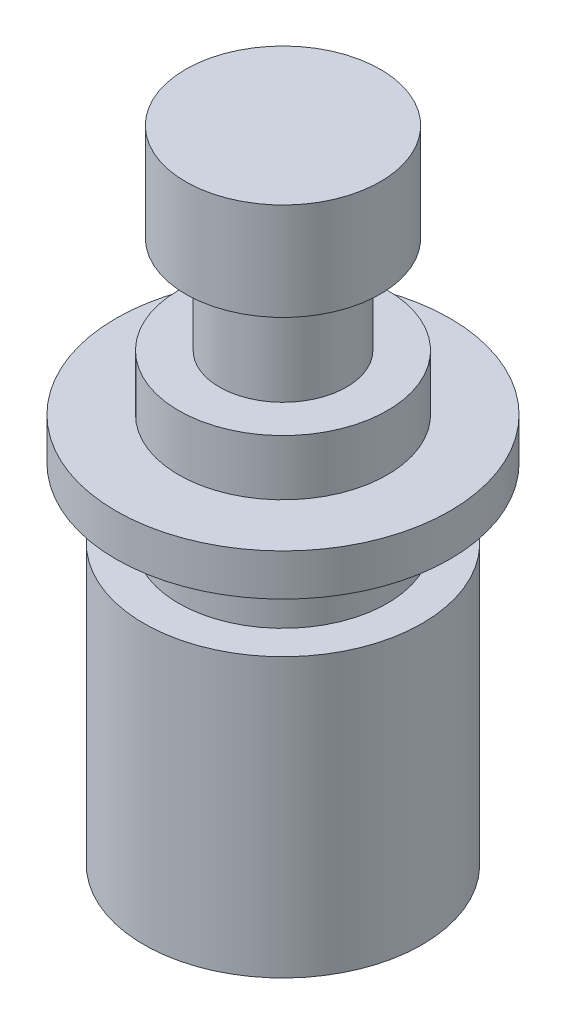
SolidWorks part; units mm, degrees
ref_plane "Plan de face" through (0, 0, 0) normal (0, 0, 1) x (1, 0, 0)
ref_plane "Plan de dessus" through (0, 0, 0) normal (0, 1, 0) x (1, 0, 0)
ref_plane "Plan de droite" through (0, 0, 0) normal (1, 0, 0) x (0, 0, -1)
sketch "Esquisse1" plane through (0, 0, 0) normal (0, 0, 1) x (1, 0, 0)
  line L0 (0, -72.5172) -> (0, -95.5172) construction
  line L1 (0, -72.5172) -> (3.5, -72.5172)
  line L2 (3.5, -72.5172) -> (3.5, -76.0172)
  line L3 (3.5, -76.0172) -> (2.2858, -76.0172)
  line L4 (2.2858, -76.0172) -> (2.2858, -79.5172)
  line L5 (2.2858, -79.5172) -> (3.75, -79.5172)
  line L6 (3.75, -79.5172) -> (3.75, -81.5172)
  line L7 (3.75, -81.5172) -> (6, -81.5172)
  line L8 (6, -81.5172) -> (6, -83.0172)
  line L9 (6, -83.0172) -> (3.75, -83.0172)
  line L10 (3.75, -83.0172) -> (3.75, -85.5172)
  line L11 (3.75, -85.5172) -> (5, -85.5172)
  line L12 (5, -85.5172) -> (5, -95.5172)
  line L13 (5, -95.5172) -> (0, -95.5172)
  line L14 (0, -72.5172) -> (0, -95.5172)
  dimension "D1" = 3.75
  dimension "D2" = 23
  dimension "D3" = 5
  dimension "D4" = 3.5
  dimension "D5" = 6
  dimension "D6" = 1.5
  dimension "D7" = 6
  dimension "D8" = 7
  dimension "D9" = 3.5
  dimension "D10" = 2.5
revolve "Révolution1" add sketch "Esquisse1" angle 360 about L0
